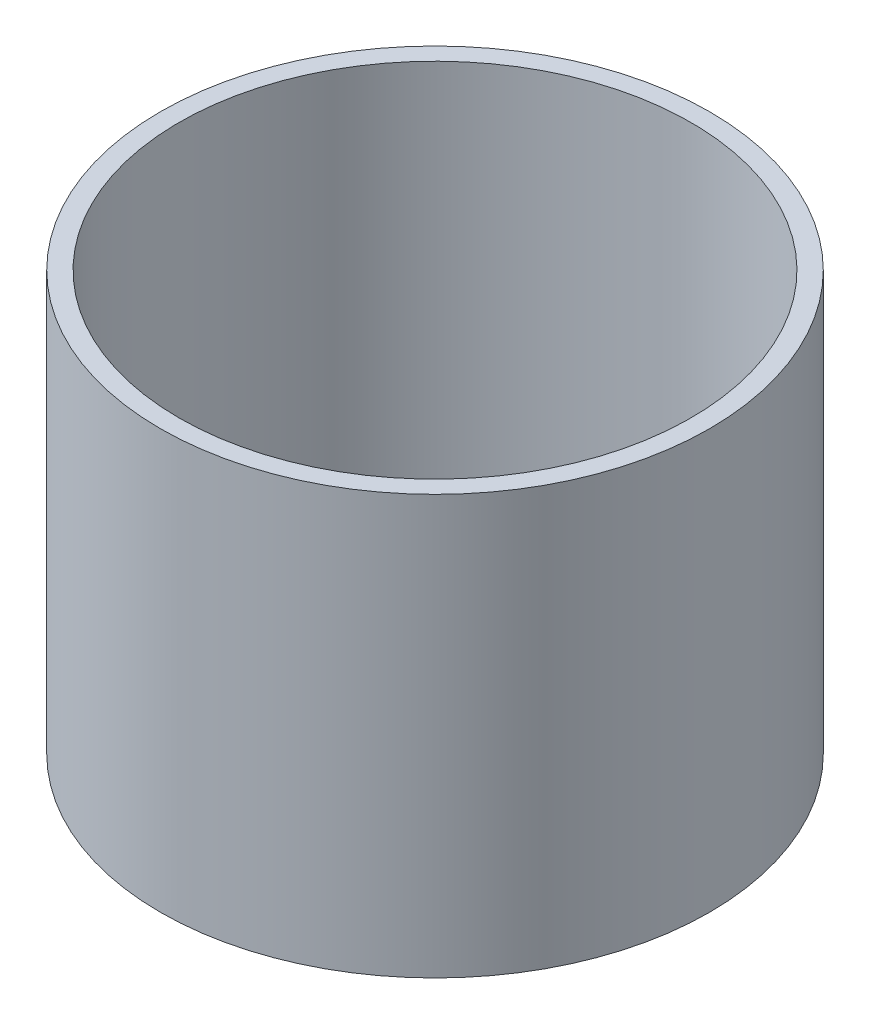
SolidWorks part; units mm, degrees
ref_plane "Front Plane" through (0, 0, 0) normal (0, 0, 1) x (1, 0, 0)
ref_plane "Top Plane" through (0, 0, 0) normal (0, 1, 0) x (1, 0, 0)
ref_plane "Right Plane" through (0, 0, 0) normal (1, 0, 0) x (0, 0, -1)
sketch "Sketch1" plane through (0, 0, 0) normal (0, 1, 0) x (1, 0, 0)
  circle A0 centre (0, 0) radius 118
  dimension "D1" = 236
extrude "Boss-Extrude1" add sketch "Sketch1" along normal blind 180
sketch "Sketch3" plane through (0, 180, 0) normal (0, 1, 0) x (1, 0, 0)
  circle A0 centre (0, 0) radius 110
  dimension "D1" = 220
extrude "Cut-Extrude1" cut sketch "Sketch3" against normal offset from surface (172 mm away) 8 up to face at (0, 0, 118)
sketch "Sketch6" plane through (0, 8, 0) normal (0, 1, 0) x (1, 0, 0)
  line L1 (-9.885, 22.915) -> (9.885, 22.915)
  line L2 (-9.885, 22.915) -> (-9.885, -22.915)
  line L3 (-9.885, -22.915) -> (9.885, -22.915)
  line L4 (9.885, 22.915) -> (9.885, -22.915)
  line L5 (0, -22.915) -> (0, 22.915) construction
  line L6 (-9.885, 0) -> (9.885, 0) construction
  point P0 (0, 0)
  dimension "D1" = 19.77
  dimension "D2" = 45.83
  dimension "D3" = 45.83
extrude "Cut-Extrude2" cut sketch "Sketch6" against normal through all
sketch "Sketch7" plane through (0, 0, 0) normal (0, -1, 0) x (1, 0, 0)
  line L1 (-8.2017, 57.0914) -> (8.416, 57.0914)
  line L2 (-8.2017, 57.0914) -> (-8.2017, 32.0914)
  line L3 (-8.2017, 32.0914) -> (8.416, 32.0914)
  line L4 (8.416, 57.0914) -> (8.416, 32.0914)
  line L5 (0.1072, 32.0914) -> (0.1072, 57.0914) construction
  line L6 (-8.2017, 44.5914) -> (8.416, 44.5914) construction
  point P0 (0.1072, 44.5914)
extrude "Cut-Extrude3" cut sketch "Sketch7" against normal blind 158
